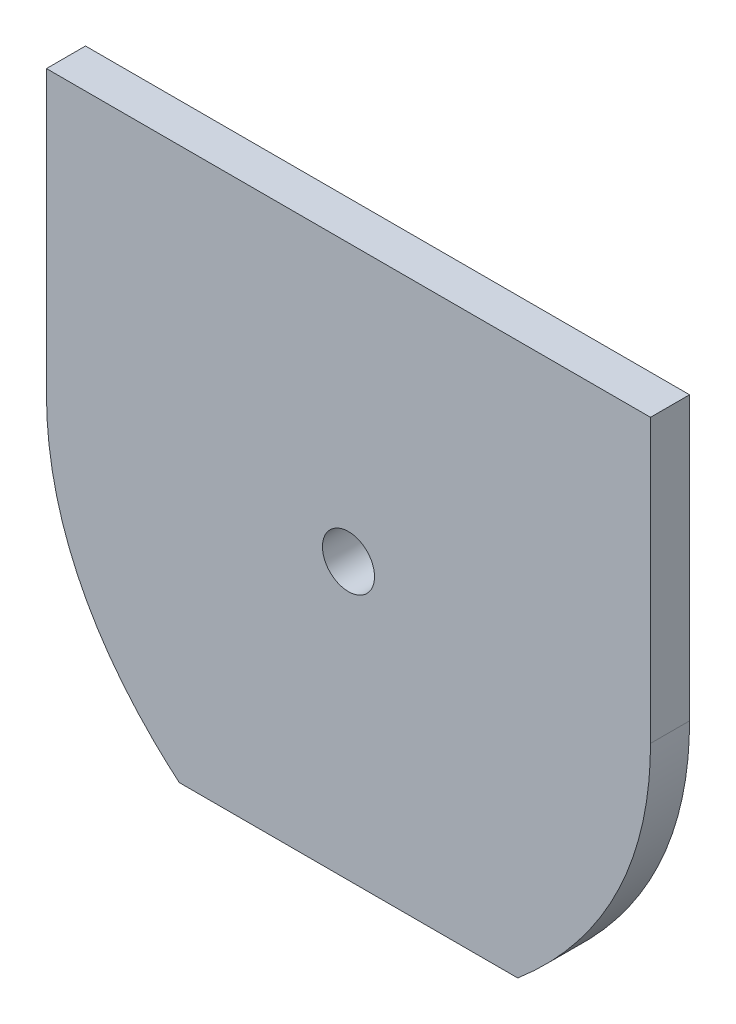
SolidWorks part; units mm, degrees
material "S-Glass Fiber"
ref_plane "Front Plane" through (0, 0, 0) normal (0, 0, 1) x (1, 0, 0)
ref_plane "Top Plane" through (0, 0, 0) normal (0, 1, 0) x (1, 0, 0)
ref_plane "Right Plane" through (0, 0, 0) normal (1, 0, 0) x (0, 0, -1)
sketch "Sketch1" plane through (0, 0, 0) normal (0, 0, 1) x (1, 0, 0)
  line L0 (0, 0) -> (0, 10.6) construction
  line L1 (-3.25, 0) -> (3.25, 0)
  line L2 (-5.8, 10.6) -> (5.8, 10.6)
  line L3 (-5.8, 10.6) -> (-5.8, 5.1767)
  line L4 (5.8, 10.6) -> (5.8, 5.1767)
  spline S0 degree 3 poles (-5.8, 5.1767) (-5.8, 3.0336) (-4.7951, 1.3114) (-3.25, 0) knots 0 0 0 0 1 1 1 1
  spline S1 degree 3 poles (5.8, 5.1767) (5.8, 3.0336) (4.7951, 1.3114) (3.25, 0) knots 0 0 0 0 1 1 1 1
  dimension "D1" = 10.6
  dimension "D2" = 11.6
  dimension "D3" = 6.5
extrude "Boss-Extrude1" add sketch "Sketch1" along normal blind 0.75
sketch "Sketch2" plane through (0, 0, 0.75) normal (0, 0, 1) x (1, 0, 0)
  line L0 (0, 0) -> (0, 10.6) construction
  line L1 (5.8, 10.6) -> (-5.8, 10.6) construction
  circle A0 centre (0, 5.3) radius 0.5
  dimension "D1" = 1
extrude "Cut-Extrude1" cut sketch "Sketch2" against normal up to next
